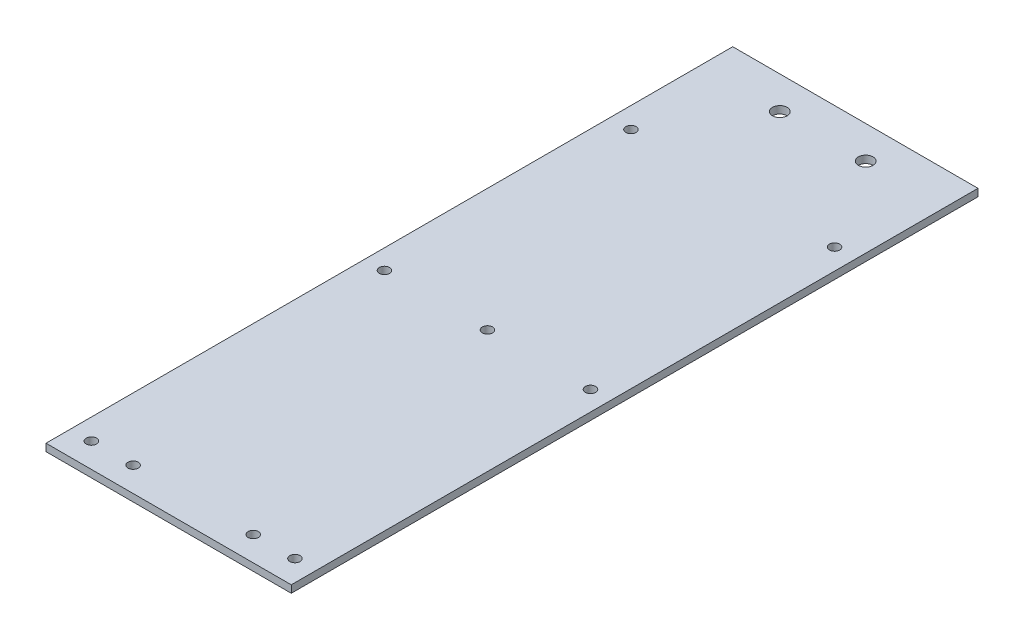
SolidWorks part; units mm, degrees
ref_plane "Front Plane" through (0, 0, 0) normal (0, 0, 1) x (1, 0, 0)
ref_plane "Top Plane" through (0, 0, 0) normal (0, 1, 0) x (1, 0, 0)
ref_plane "Right Plane" through (0, 0, 0) normal (1, 0, 0) x (0, 0, -1)
sketch "Sketch1" plane through (0, 0, 0) normal (0, 1, 0) x (1, 0, 0)
  line L1 (-50, 60) -> (50, 60)
  line L2 (-50, 60) -> (-50, -60)
  line L3 (-50, -60) -> (50, -60)
  line L4 (50, 60) -> (50, -60)
  line L5 (-50, 60) -> (50, -60) construction
  line L6 (-50, -60) -> (50, 60) construction
  line L7 (71.831, 0) -> (-33.8294, 0) construction
  line L8 (0, 117.1606) -> (0, -73.5833) construction
  circle A1 centre (41.5, -50) radius 2.1
  circle A2 centre (-41.5, -50) radius 2.1
  circle A4 centre (-42, 70) radius 2.1
  circle A5 centre (0, 70) radius 2.1
  circle A6 centre (42, 70) radius 2.1
  point P0 (0, 0)
  dimension "D3" = 130
  dimension "D8" = 4.2
  dimension "D1" = 100
  dimension "D2" = 120
  dimension "D6" = 60
  dimension "D7" = 50
extrude "Boss-Extrude1" add sketch "Sketch1" along normal blind 3
sketch "Sketch2" plane through (0, 0, 0) normal (0, -1, 0) x (1, 0, 0)
  line L0 (-50, -60) -> (-50, 60) construction
  line L1 (-50, 60) -> (50, 60) construction
  circle A2 centre (24.5, 50) radius 2.1
  circle A3 centre (-24.5, 50) radius 2.1
  dimension "D1" = 25.5
  dimension "D2" = 10
  dimension "D3" = 49
  dimension "D4" = 4.2
extrude "Cut-Extrude1" cut sketch "Sketch2" against normal blind 10
sketch "Sketch3" plane through (0, 0, -60) normal (0, 0, -1) x (-1, 0, 0)
  line L1 (50, 0) -> (-50, 0)
  line L2 (50, 0) -> (50, 3)
  line L3 (50, 3) -> (-50, 3)
  line L4 (-50, 0) -> (-50, 3)
extrude "Boss-Extrude2" add sketch "Sketch3" along normal blind 160
sketch "Sketch4" plane through (0, 0, 0) normal (0, -1, 0) x (1, 0, 0)
  line L0 (50, 60) -> (50, -220) construction
  line L1 (-50, -220) -> (-50, 60) construction
  line L3 (50, -220) -> (-50, -220) construction
  circle A0 centre (17.5, -206.7) radius 3
  circle A1 centre (-17.5, -206.7) radius 3
  circle A2 centre (-41.5, -170) radius 2.1
  circle A5 centre (41.5, -170) radius 2.1
  dimension "D1" = 4.2
  dimension "D2" = 6
  dimension "D5" = 50
  dimension "D6" = 32.5
  dimension "D7" = 32.5
  dimension "D8" = 13.3
  dimension "D3" = 8.5
  dimension "D4" = 8.5
extrude "Cut-Extrude2" cut sketch "Sketch4" against normal blind 160
sketch "Sketch5" plane through (0, 0, 0) normal (0, -1, 0) x (1, 0, 0)
  circle A0 centre (-42, -70) radius 2.1
  circle A1 centre (0, -70) radius 2.1
  circle A2 centre (42, -70) radius 2.1
  dimension "D1" = 4.2
extrude "Cut-Extrude3" cut sketch "Sketch5" against normal blind 10
sketch "Sketch6" plane through (0, 0, 0) normal (0, -1, 0) x (1, 0, 0)
  line L0 (-50, -220) -> (-50, 60) construction
  line L1 (-50, 60) -> (50, 60) construction
  line L3 (50, 60) -> (50, -220) construction
  circle A0 centre (-16, -25) radius 1.414
  circle A1 centre (-32, -25) radius 1.4755
  circle A2 centre (30, 13) radius 2.5
  circle A3 centre (10, 13) radius 2.6
  circle A4 centre (20, 30) radius 1.75
  dimension "D1" = 34
  dimension "D2" = 16
  dimension "D4" = 20
  dimension "D5" = 5
  dimension "D6" = 47
  dimension "D7" = 40
  dimension "D8" = 30
  dimension "D9" = 30
  dimension "D3" = 85
